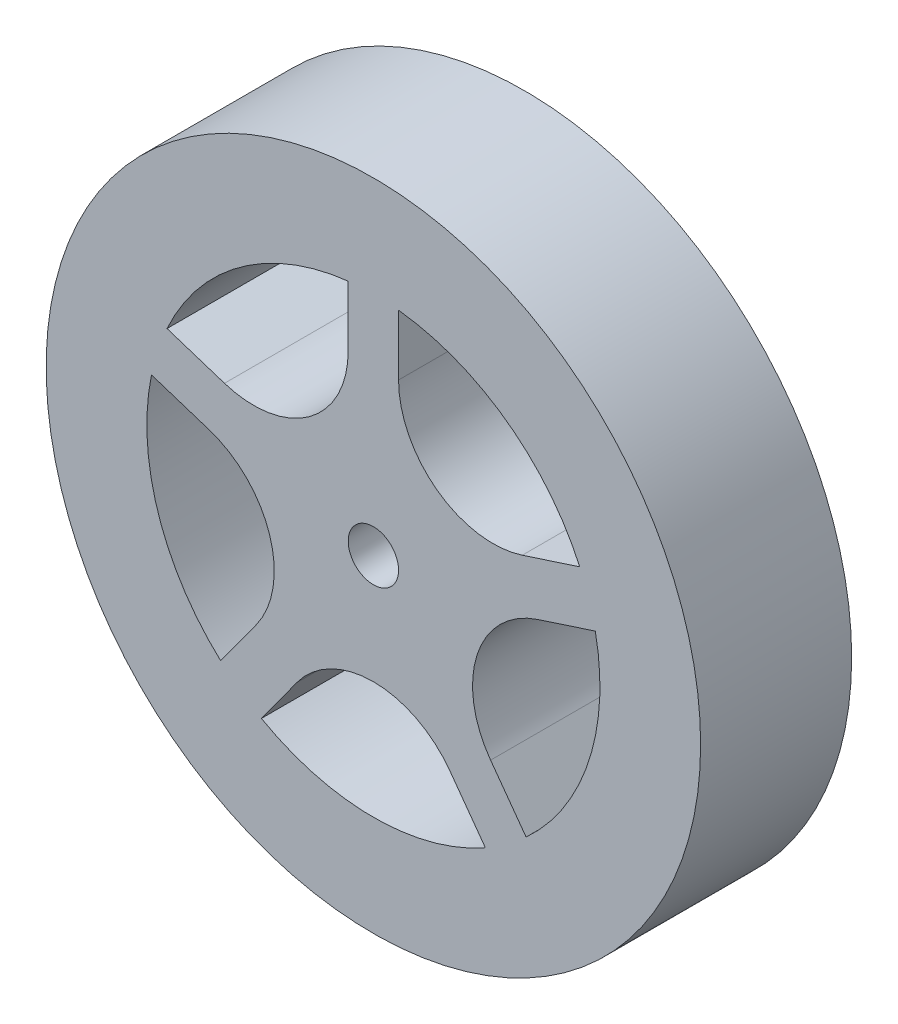
SolidWorks part; units mm, degrees
ref_plane "前基準面" through (0, 0, 0) normal (0, 0, 1) x (1, 0, 0)
ref_plane "上基準面" through (0, 0, 0) normal (0, 1, 0) x (1, 0, 0)
ref_plane "右基準面" through (0, 0, 0) normal (1, 0, 0) x (0, 0, -1)
sketch "草圖1" plane through (0, 0, 0) normal (0, 0, 1) x (1, 0, 0)
  line L0 (0, 0) -> (0, 22.5) construction
  line L1 (0, 0) -> (21.3988, 6.9529) construction
  line L2 (0, 0) -> (13.2252, -18.2029) construction
  line L3 (0, 0) -> (-13.2252, -18.2029) construction
  line L4 (0, 0) -> (-21.3988, 6.9529) construction
  line L5 (-2.5, 22.3607) -> (-2.5, 16.3607)
  line L6 (2.5, 22.3607) -> (2.5, 16.3607)
  line L7 (22.0388, 4.5322) -> (16.3325, 2.6781)
  line L8 (20.4937, 9.2875) -> (14.7874, 7.4334)
  line L9 (11.1207, -19.5596) -> (7.594, -14.7055)
  line L10 (15.1658, -16.6207) -> (11.6391, -11.7666)
  line L11 (-15.1658, -16.6207) -> (-11.6391, -11.7666)
  line L12 (-11.1207, -19.5596) -> (-7.594, -14.7055)
  line L13 (-20.4937, 9.2875) -> (-14.7874, 7.4334)
  line L14 (-22.0388, 4.5322) -> (-16.3325, 2.6781)
  circle A0 centre (0, 0) radius 32.5
  arc A2 (-22.0388, 4.5322) -> (-15.1658, -16.6207) centre (0, 0) ccw
  arc A3 (-14.7874, 7.4334) -> (-2.5, 16.3607) centre (-11.8867, 16.3607) ccw
  arc A4 (-16.3325, 2.6781) -> (-11.6391, -11.7666) centre (-19.2331, -6.2492) cw
  arc A5 (-7.594, -14.7055) -> (7.594, -14.7055) centre (0, -20.2229) cw
  arc A6 (2.5, 16.3607) -> (14.7874, 7.4334) centre (11.8867, 16.3607) ccw
  arc A7 (11.6391, -11.7666) -> (16.3325, 2.6781) centre (19.2331, -6.2492) cw
  circle A8 centre (0, 0) radius 22.5 construction
  arc A9 (-2.5, 22.3607) -> (-20.4937, 9.2875) centre (0, 0) ccw
  arc A10 (20.4937, 9.2875) -> (2.5, 22.3607) centre (0, 0) ccw
  arc A11 (15.1658, -16.6207) -> (22.0388, 4.5322) centre (0, 0) ccw
  arc A12 (-11.1207, -19.5596) -> (11.1207, -19.5596) centre (0, 0) ccw
  circle A13 centre (0, 0) radius 2.5
  point P13 (0, 0)
  point P33 (0, 0)
  dimension "D1" = 65
  dimension "D2" = 10
  dimension "D7" = 5
  dimension "D3" = 5
  dimension "D4" = 5
  dimension "D5" = 6
  dimension "D6" = 5
extrude "填料-伸長1" add sketch "草圖1" along normal blind 15
